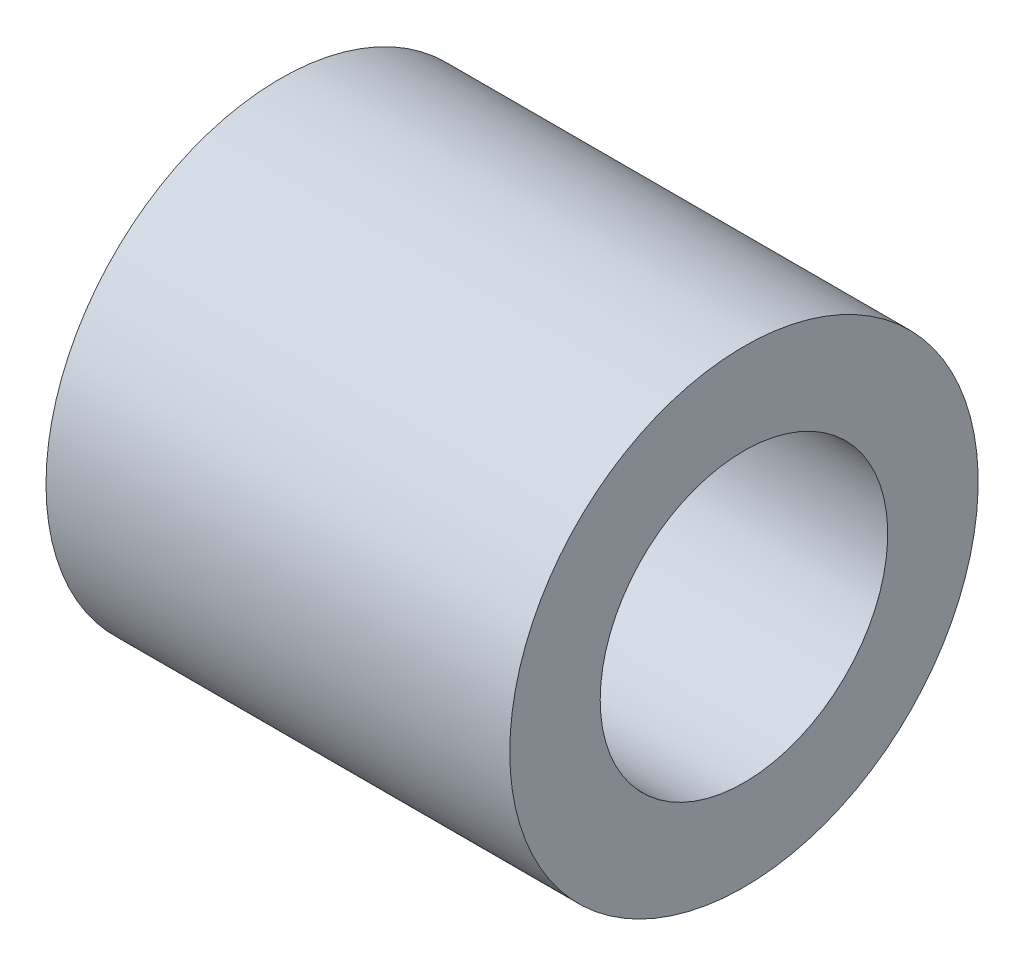
SolidWorks part; units mm, degrees
ref_plane "Front Plane" through (0, 0, 0) normal (0, 0, 1) x (1, 0, 0)
ref_plane "Top Plane" through (0, 0, 0) normal (0, 1, 0) x (1, 0, 0)
ref_plane "Right Plane" through (0, 0, 0) normal (1, 0, 0) x (0, 0, -1)
sketch "Sketch1" plane through (0, 0, 0) normal (0, 0, 1) x (1, 0, 0)
  line L0 (0, 0) -> (15.24, 0) construction
  line L1 (0, 3.937) -> (12.7, 3.937)
  line L2 (0, 3.937) -> (0, 6.4135)
  line L3 (0, 6.4135) -> (12.7, 6.4135)
  line L4 (12.7, 3.937) -> (12.7, 6.4135)
  point P5 (36.2094, 3.937)
  point P9 (15.24, 0)
  dimension "D1" = 12.827
  dimension "D2" = 7.874
  dimension "D3" = 12.7
revolve "Revolve1" add sketch "Sketch1" angle 360 about L0
